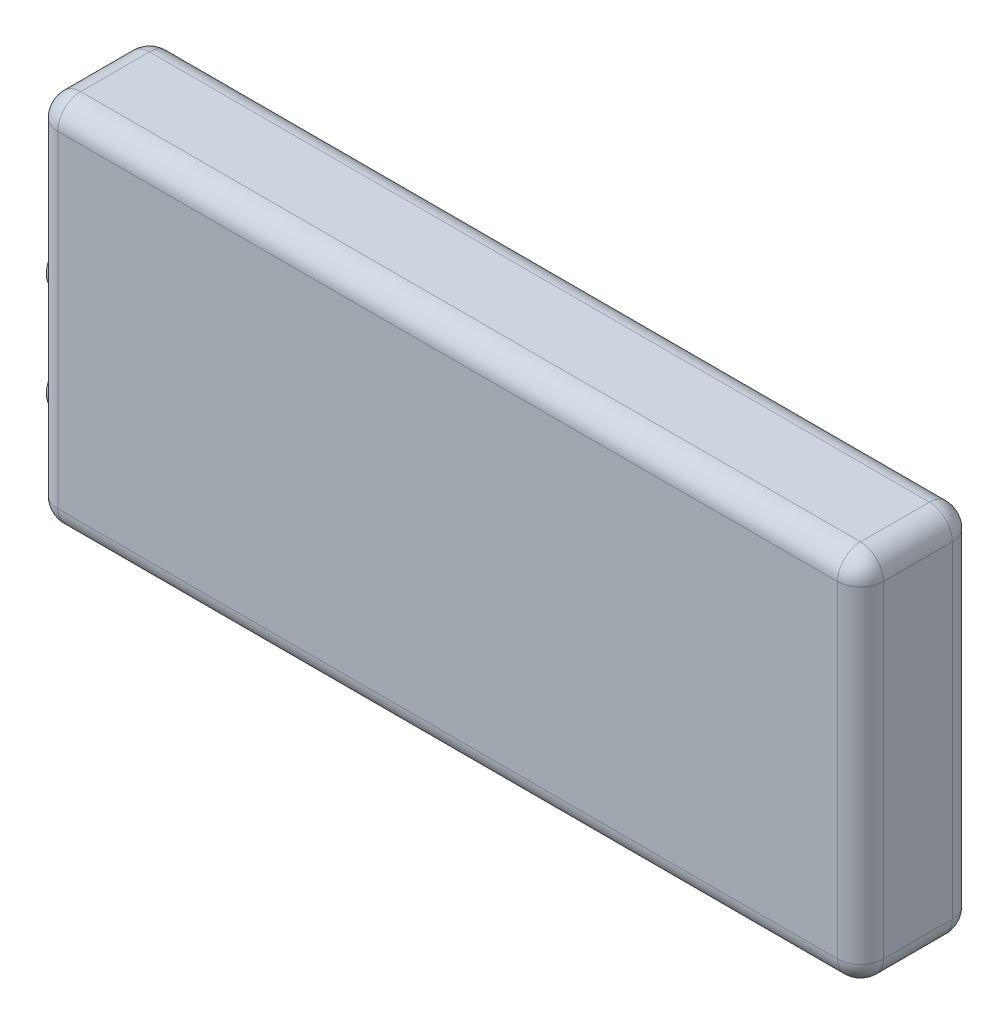
SolidWorks part; units mm, degrees
ref_plane "Front Plane" through (0, 0, 0) normal (0, 0, 1) x (1, 0, 0)
ref_plane "Top Plane" through (0, 0, 0) normal (0, 1, 0) x (1, 0, 0)
ref_plane "Right Plane" through (0, 0, 0) normal (1, 0, 0) x (0, 0, -1)
sketch "Sketch1" plane through (0, 0, 0) normal (0, 0, 1) x (1, 0, 0)
  line L1 (-36, 16.25) -> (36, 16.25)
  line L2 (-36, 16.25) -> (-36, -16.25)
  line L3 (-36, -16.25) -> (36, -16.25)
  line L4 (36, 16.25) -> (36, -16.25)
  line L5 (-36, 16.25) -> (36, -16.25) construction
  line L6 (-36, -16.25) -> (36, 16.25) construction
  point P0 (0, 0)
extrude "Boss-Extrude1" add sketch "Sketch1" along normal blind 10
fillet "Fillet2" radius 2 12 edges at (36, -16.25, 5) (36, 16.25, 5) (36, 0, 0) (36, 0, 10) (-36, 0, 0) (-36, 0, 10) (-36, 16.25, 5) (-36, -16.25, 5) (0, -16.25, 10) (0, -16.25, 0) (0, 16.25, 0) (0, 16.25, 10)
sketch "Sketch2" plane through (-36, 0, 0) normal (-1, 0, 0) x (0, 0, 1)
  line L0 (2, 14.25) -> (8, 14.25)
  line L1 (2, 14.25) -> (2, -14.0814)
  line L2 (8, 14.25) -> (8, -14.0814)
  line L3 (2, -14.0814) -> (8, -14.0814)
  circle A0 centre (5, 0) radius 2
  circle A1 centre (5, -9.0405) radius 3
  circle A2 centre (5, 0) radius 3
  circle A3 centre (5, -9.0405) radius 2
extrude "Cut-Extrude1" cut sketch "Sketch2" against normal blind 3 contours A2 A0 | A1 A3
sketch "Sketch3" plane through (-36, 0, 0) normal (-1, 0, 0) x (0, 0, 1)
  circle A0 centre (5, -9.0405) radius 2
  circle A1 centre (5, 0) radius 2
extrude "Boss-Extrude2" add sketch "Sketch3" along normal blind 2
sketch "Sketch4" plane through (0, 0, 0) normal (0, 0, -1) x (-1, 0, 0)
  text T0 "<b>ESC</b>"
extrude "Cut-Extrude2" cut sketch "Sketch4" against normal blind 1
